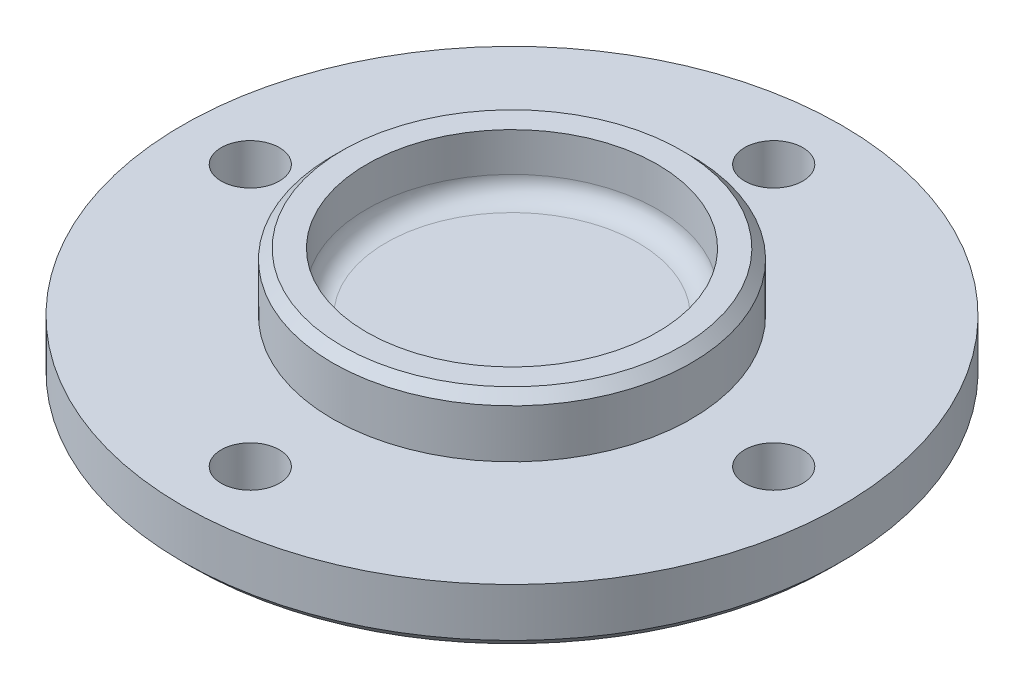
SolidWorks part; units mm, degrees
ref_plane "前视基准面" through (0, 0, 0) normal (0, 0, 1) x (1, 0, 0)
ref_plane "上视基准面" through (0, 0, 0) normal (0, 1, 0) x (1, 0, 0)
ref_plane "右视基准面" through (0, 0, 0) normal (1, 0, 0) x (0, 0, -1)
other "Configuration Table"
sketch "草图1" plane through (0, 0, 0) normal (0, 1, 0) x (1, 0, 0)
  circle A0 centre (0, 0) radius 34
  dimension "D1" = 68
extrude "凸台-拉伸1" add sketch "草图1" along normal blind 6
sketch "草图2" plane through (0, 6, 0) normal (0, 1, 0) x (1, 0, 0)
  circle A0 centre (0, 0) radius 18.5
  circle A1 centre (0, 0) radius 15
  dimension "D1" = 37
  dimension "D2" = 30
extrude "凸台-拉伸2" add sketch "草图2" along normal blind 6
sketch "草图5" plane through (0, 6, 0) normal (0, 1, 0) x (1, 0, 0)
  circle A0 centre (0, 27) radius 3
  dimension "D1" = 6
  dimension "D2" = 27
extrude "切除-拉伸1" cut sketch "草图5" against normal blind 6
pattern_circular "阵列(圆周)1" count 4 over 360 about axis through (0, 0, 0) along (0, 1, 0) of "切除-拉伸1"
fillet "圆角1" radius 2 1 edges at (0, 6, 15)
chamfer "倒角1" distance 1 angle 45 2 edges at (0, 0, 34) (0, 12, 18.5)
